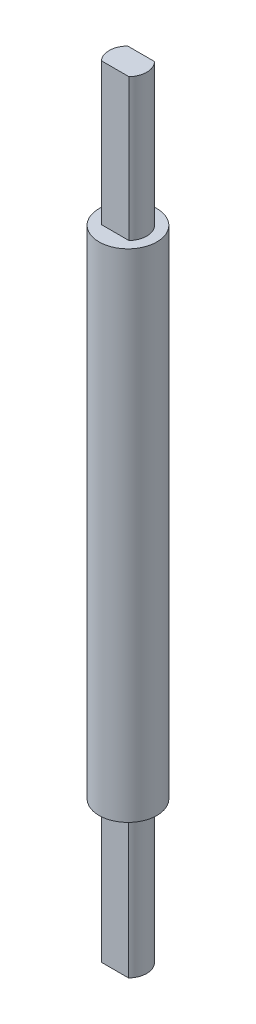
SolidWorks part; units mm, degrees
ref_plane "Front Plane" through (0, 0, 0) normal (0, 0, 1) x (1, 0, 0)
ref_plane "Top Plane" through (0, 0, 0) normal (0, 1, 0) x (1, 0, 0)
ref_plane "Right Plane" through (0, 0, 0) normal (1, 0, 0) x (0, 0, -1)
sketch "Sketch1" plane through (0, 0, 0) normal (0, 1, 0) x (1, 0, 0)
  line L0 (1.9076, 1.825) -> (-1.9076, 1.825)
  line L1 (-1.9076, -1.825) -> (1.9076, -1.825)
  arc A0 (-1.9076, 1.825) -> (-1.9076, -1.825) centre (0, 0) ccw
  arc A1 (1.9076, -1.825) -> (1.9076, 1.825) centre (0, 0) ccw
  dimension "D1" = 5.28
  dimension "D2" = 3.65
  dimension "D3" = 1.825
  dimension "D4" = 1.825
extrude "Boss-Extrude1" add sketch "Sketch1" along normal blind 20
sketch "Sketch2" plane through (0, 20, 0) normal (0, 1, 0) x (1, 0, 0)
  circle A0 centre (0, 0) radius 4.075
  dimension "D1" = 8.15
extrude "Boss-Extrude2" add sketch "Sketch2" along normal blind 70
sketch "Sketch3" plane through (0, 90, 0) normal (0, 1, 0) x (1, 0, 0)
  line L0 (1.8974, 1.85) -> (-1.8974, 1.85)
  line L1 (1.9449, -1.8) -> (-1.9449, -1.8)
  arc A0 (-1.8974, 1.85) -> (-1.9449, -1.8) centre (0, 0) ccw
  arc A1 (1.9449, -1.8) -> (1.8974, 1.85) centre (0, 0) ccw
  dimension "D1" = 5.3
  dimension "D2" = 3.65
  dimension "D3" = 1.8
extrude "Boss-Extrude3" add sketch "Sketch3" along normal blind 20
